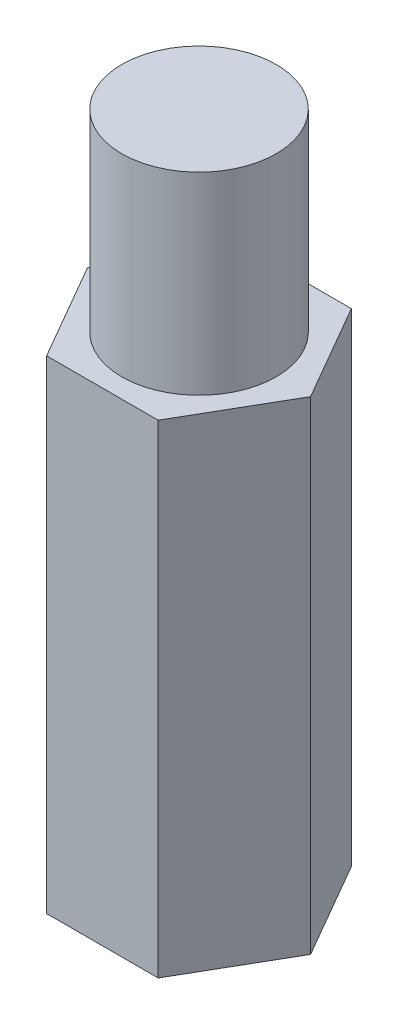
SolidWorks part; units mm, degrees
ref_plane "前视基准面" through (0, 0, 0) normal (0, 0, 1) x (1, 0, 0)
ref_plane "上视基准面" through (0, 0, 0) normal (0, 1, 0) x (1, 0, 0)
ref_plane "右视基准面" through (0, 0, 0) normal (1, 0, 0) x (0, 0, -1)
other "Configuration Table"
sketch "草图1" plane through (0, 0, 0) normal (0, 1, 0) x (1, 0, 0)
  line L1 (2.3094, 0) -> (1.1547, 2)
  line L2 (1.1547, 2) -> (-1.1547, 2)
  line L3 (-1.1547, 2) -> (-2.3094, 0)
  line L4 (-2.3094, 0) -> (-1.1547, -2)
  line L5 (-1.1547, -2) -> (1.1547, -2)
  line L6 (1.1547, -2) -> (2.3094, 0)
  circle A0 centre (0, 0) radius 2 construction
  dimension "D1" = 4
extrude "凸台-拉伸1" add sketch "草图1" along normal blind 10
sketch "草图2" plane through (0, 10, 0) normal (0, 1, 0) x (1, 0, 0)
  circle A0 centre (0, 0) radius 1.6
extrude "凸台-拉伸2" add sketch "草图2" along normal blind 4
sketch "草图3" plane through (0, 0, 0) normal (0, -1, 0) x (1, 0, 0)
  circle A0 centre (0, 0) radius 1.6
extrude "切除-拉伸1" cut sketch "草图3" against normal blind 4
